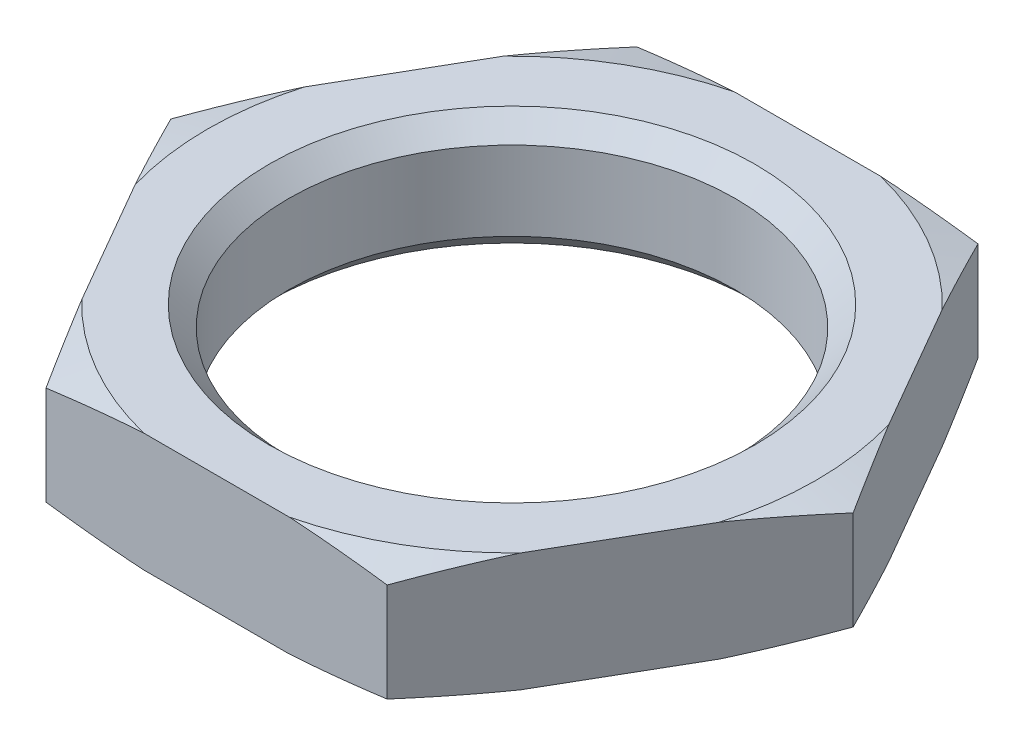
SolidWorks part; units mm, degrees
ref_plane "Plan1" through (0, 0, 0) normal (0, 0, 1) x (1, 0, 0)
ref_plane "Plan2" through (0, 0, 0) normal (0, 1, 0) x (1, 0, 0)
ref_plane "Plan3" through (0, 0, 0) normal (1, 0, 0) x (0, 0, -1)
sketch "Esquisse1" plane through (0, 0, 0) normal (0, 1, 0) x (1, 0, 0)
  line L0 (8.6314, 14.95) -> (17.2628, 0)
  line L1 (17.2628, 0) -> (8.6314, -14.95)
  line L2 (8.6314, -14.95) -> (-8.6314, -14.95)
  line L3 (-8.6314, -14.95) -> (-17.2628, 0)
  line L4 (-17.2628, 0) -> (-8.6314, 14.95)
  line L5 (-8.6314, 14.95) -> (8.6314, 14.95)
  line L6 (-50, 0) -> (50, 0) construction
  line L8 (0, 14.95) -> (0, -27.2638) construction
  line L9 (0, -50) -> (0, 50) construction
  circle A0 centre (0, 0) radius 11.3
  dimension "D3" = 22.6
  dimension "D1" = 120
  dimension "D2" = 29.9
extrude "Base-Extrusion" add sketch "Esquisse1" along normal mid plane 6
chamfer "Chanfrein1" distance 1 angle 45
sketch "Esquisse2" plane through (0, 0, 0) normal (0, 0, 1) x (1, 0, 0)
  line L0 (-14.95, 0) -> (14.95, 0) construction
  line L3 (15.3967, 3) -> (17.2628, 2.5)
  line L5 (17.2628, 2.5) -> (17.2628, 3)
  line L6 (17.2628, 3) -> (15.3967, 3)
  line L7 (17.2628, -3) -> (15.3967, -3)
  line L8 (17.2628, -2.5) -> (17.2628, -3)
  line L9 (15.3967, -3) -> (17.2628, -2.5)
  line L10 (0, 0) -> (0, -5.3044) construction
  line L13 (17.2628, 3) -> (17.2628, -3) construction
  line L14 (8.6314, 3) -> (17.2628, 3) construction
  dimension "D1" = 0.5
  dimension "D2" = 15
revolve "Enlèvement de matière-Révolution3" cut sketch "Esquisse2" angle 360 about L10
